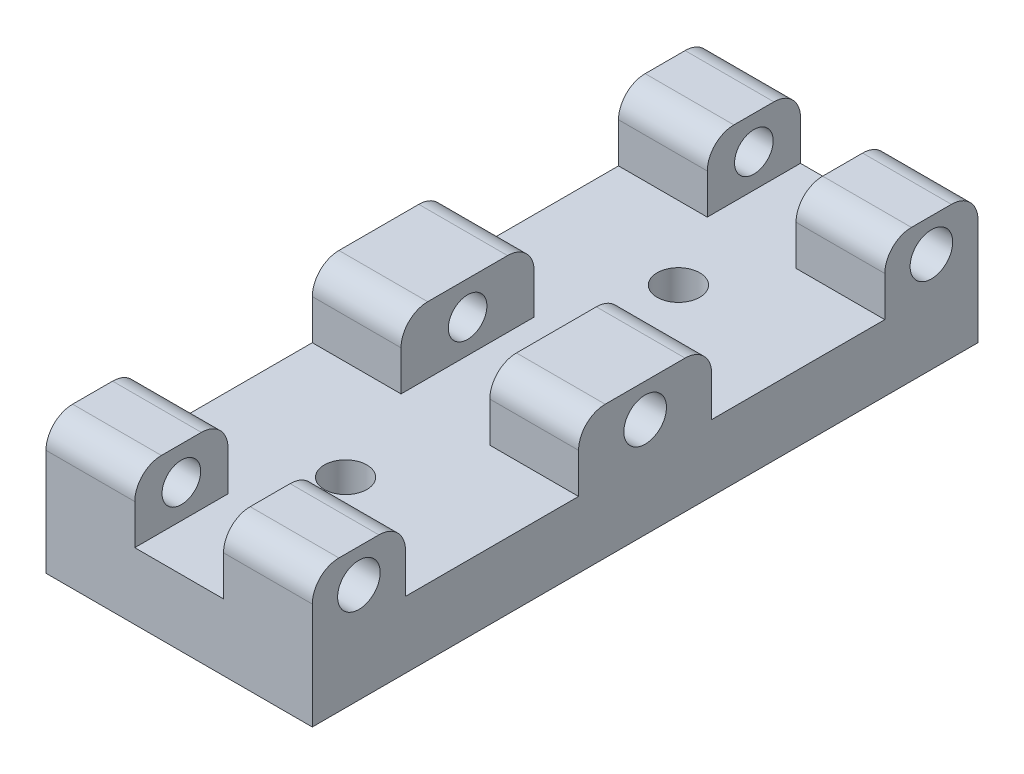
SolidWorks part; units mm, degrees
ref_plane "Front Plane" through (0, 0, 0) normal (0, 0, 1) x (1, 0, 0)
ref_plane "Top Plane" through (0, 0, 0) normal (0, 1, 0) x (1, 0, 0)
ref_plane "Right Plane" through (0, 0, 0) normal (1, 0, 0) x (0, 0, -1)
other "Configuration Table"
sketch "Sketch1" plane through (0, 0, 0) normal (0, 1, 0) x (1, 0, 0)
  line L1 (-10, 25) -> (10, 25)
  line L2 (-10, 25) -> (-10, -25)
  line L3 (-10, -25) -> (10, -25)
  line L4 (10, 25) -> (10, -25)
  line L5 (-10, 25) -> (10, -25) construction
  line L6 (-10, -25) -> (10, 25) construction
  point P0 (0, 0)
  dimension "D1" = 20
  dimension "D2" = 50
extrude "Boss-Extrude1" add sketch "Sketch1" along normal blind 5
sketch "Sketch2" plane through (0, 5, 0) normal (0, 1, 0) x (1, 0, 0)
  line L0 (0, 12.5) -> (0, -12.5) construction
  circle A0 centre (0, 12.5) radius 1.6
  circle A1 centre (0, -12.5) radius 1.6
  point P4 (0, 0)
  dimension "D2" = 3.2
  dimension "D1" = 25
extrude "Cut-Extrude1" cut sketch "Sketch2" against normal through all
sketch "Sketch3" plane through (0, 5, 0) normal (0, 1, 0) x (1, 0, 0)
  line L0 (0, 0) -> (0, -5) construction
  line L1 (0, 0) -> (0, 5) construction
  line L2 (-10, -5) -> (10, -5)
  line L3 (10, -25) -> (10, 25) construction
  line L4 (-10, 5) -> (10, 5)
  line L5 (10, 5) -> (10, -5)
  line L6 (-10, -5) -> (-10, 5)
  line L7 (0, -25) -> (0, -18) construction
  line L8 (-10, -25) -> (10, -25) construction
  line L9 (0, 25) -> (0, 18) construction
  line L10 (10, 25) -> (-10, 25) construction
  line L11 (-10, -18) -> (10, -18)
  line L12 (10, -18) -> (10, -25)
  line L13 (10, -25) -> (-10, -25)
  line L14 (-10, -25) -> (-10, -18)
  line L15 (-10, 18) -> (10, 18)
  line L16 (10, 18) -> (10, 25)
  line L17 (10, 25) -> (-10, 25)
  line L18 (-10, 25) -> (-10, 18)
  point P10 (0, -5)
  point P12 (0, 5)
  point P23 (0, -18)
  point P30 (0, 18)
  dimension "D1" = 10
  dimension "D2" = 7
extrude "Boss-Extrude2" add sketch "Sketch3" along normal blind 5
sketch "Sketch4" plane through (-10, 0, 0) normal (-1, 0, 0) x (0, 0, 1)
  line L0 (-18, 10) -> (-25, 5) construction
  line L1 (-25, 10) -> (-25, 0) construction
  line L2 (-5, 10) -> (5, 5) construction
  line L3 (25, 10) -> (18, 5) construction
  circle A0 centre (-21.5, 7.5) radius 1.45
  circle A1 centre (0, 7.5) radius 1.45
  circle A2 centre (21.5, 7.5) radius 1.45
  dimension "D1" = 2.9
extrude "Cut-Extrude2" cut sketch "Sketch4" against normal through all
sketch "Sketch5" plane through (0, 0, -25) normal (0, 0, -1) x (-1, 0, 0)
  line L0 (-10, 10) -> (-3.3333, 10) construction
  line L1 (-10, 10) -> (10, 10) construction
  line L2 (-3.3333, 10) -> (3.3333, 10) construction
  line L3 (3.3333, 10) -> (10, 10) construction
  line L4 (-3.3333, 10) -> (-3.3333, 5)
  line L5 (-3.3333, 5) -> (3.3333, 5)
  line L6 (3.3333, 5) -> (3.3333, 10)
  line L7 (3.3333, 10) -> (-3.3333, 10)
  line L8 (-10, 5) -> (10, 5) construction
extrude "Cut-Extrude3" cut sketch "Sketch5" against normal through all
sketch "Sketch6" plane through (10, 0, 0) normal (1, 0, 0) x (0, 0, -1)
  circle A0 centre (21.5, 7.5) radius 1.6
  circle A1 centre (0, 7.5) radius 1.6
  circle A2 centre (-21.5, 7.5) radius 1.6
  dimension "D1" = 3.2
extrude "Cut-Extrude4" cut sketch "Sketch6" against normal up to next
fillet "Fillet1" radius 2 12 edges at (-6.6667, 10, -25) (6.6667, 10, -25) (6.6667, 10, -18) (-6.6667, 10, -18) (6.6667, 10, 5) (6.6667, 10, -5) (-6.6667, 10, -5) (-6.6667, 10, 5) (-6.6667, 10, 25) (-6.6667, 10, 18) (6.6667, 10, 25) (6.6667, 10, 18)
